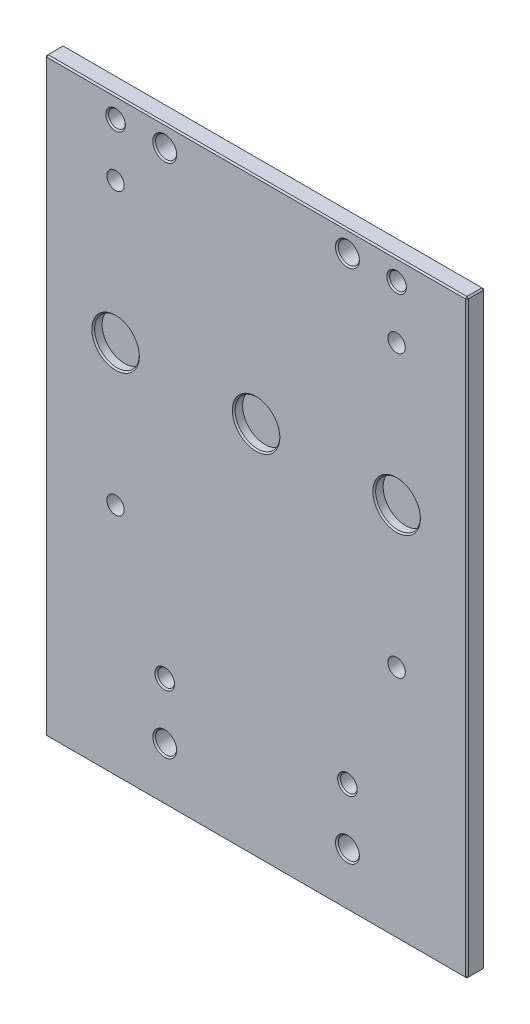
SolidWorks part; units mm, degrees
ref_plane "Front Plane" through (0, 0, 0) normal (0, 0, 1) x (1, 0, 0)
ref_plane "Top Plane" through (0, 0, 0) normal (0, 1, 0) x (1, 0, 0)
ref_plane "Right Plane" through (0, 0, 0) normal (1, 0, 0) x (0, 0, -1)
sketch "Sketch1" plane through (0, 0, 0) normal (0, 0, 1) x (1, 0, 0)
  line L2 (0, 0) -> (0, 210)
  line L3 (0, 210) -> (150, 210)
  line L4 (150, 0) -> (150, 210)
  line L7 (0, 0) -> (150, 0)
  circle A0 centre (25, 202.5) radius 2.98
  circle A1 centre (125, 202.5) radius 2.98
  circle A2 centre (42.5, 202.5) radius 3.75
  circle A3 centre (107.5, 202.5) radius 3.75
  circle A4 centre (107.5, 39) radius 2.98
  circle A5 centre (42.5, 39) radius 2.98
  circle A6 centre (42.5, 19) radius 3.75
  circle A7 centre (107.5, 19) radius 3.75
  dimension "D8" = 5.96
  dimension "D9" = 5.96
  dimension "D10" = 7.5
  dimension "D11" = 7.5
  dimension "D15" = 5.96
  dimension "D16" = 5.96
  dimension "D17" = 7.5
  dimension "D18" = 7.5
  dimension "D2" = 210
  dimension "D3" = 25
  dimension "D4" = 25
  dimension "D5" = 17.5
  dimension "D6" = 17.5
  dimension "D7" = 7.5
  dimension "D12" = 150
  dimension "D13" = 163.5
  dimension "D14" = 163.5
  dimension "D19" = 20
  dimension "D20" = 20
extrude "Boss-Extrude1" add sketch "Sketch1" along normal blind 6.35
sketch "Sketch2" plane through (0, 0, 6.35) normal (0, 0, 1) x (1, 0, 0)
  line L0 (150, 0) -> (150, 210) construction
  line L3 (0, 0) -> (150, 0) construction
  circle A0 centre (75, 133.75) radius 7.9577
  dimension "D1" = 15.9154
  dimension "D2" = 75
  dimension "D3" = 133.75
extrude "Cut-Extrude1" cut sketch "Sketch2" against normal blind 3.175
sketch "Sketch3" plane through (0, 0, 6.35) normal (0, 0, 1) x (1, 0, 0)
  circle A0 centre (25, 183.75) radius 3.1877
  circle A1 centre (125, 183.75) radius 3.1877
  circle A2 centre (125, 83.75) radius 3.1877
  circle A3 centre (25, 83.75) radius 3.1877
  circle A5 centre (75, 133.75) radius 7.9577 construction
  dimension "D1" = 6.3754
  dimension "D2" = 6.3754
  dimension "D3" = 6.3754
  dimension "D4" = 6.3754
  dimension "D9" = 50
  dimension "D8" = 50
  dimension "D10" = 50
  dimension "D5" = 50
  dimension "D6" = 50
  dimension "D7" = 50
  dimension "D11" = 50
  dimension "D12" = 50
hole_wizard "15/64 (0.23438) Diameter Hole1" positions "3DSketch1" profile "Sketch5" hole size "15/64" standard "Ansi Inch"
sketch3d "3DSketch1"
  point P0 (25, 183.75, 6.35)
  point P3 (125, 183.75, 6.35)
  point P6 (125, 83.75, 6.35)
  point P9 (25, 83.75, 6.35)
sketch "Sketch5" plane through (25, 183.75, 6.35) normal (1, 0, 0) x (0, -1, 0)
  line L0 (0, 0) -> (0, 9.2081)
  line L1 (0, 9.2081) -> (3.0924, 7.35)
  line L2 (3.0924, 7.35) -> (3.0924, 0)
  line L5 (3.0924, 0) -> (0, 0)
  line L10 (0, 9.2081) -> (-3.0925, 7.35) construction
  line L11 (0, -6.35) -> (0, 107.95) construction
  dimension "Hole Dia." = 6.1849
  dimension "Hole Depth" = 7.35
  dimension "Drill Angle" = 118
chamfer "Chamfer1" distance 0.5 angle 45 29 edges at (46.25, 202.5, 0) (27.98, 202.5, 0) (111.25, 202.5, 0) (127.98, 202.5, 0) (110.48, 39, 0) (111.25, 19, 0) (45.48, 39, 0) (46.25, 19, 0) (75, 0, 0) (0, 105, 0) (75, 210, 0) (150, 105, 0) (0, 210, 3.175) (150, 210, 3.175) (0, 0, 3.175) (150, 0, 3.175) (150, 105, 6.35) (75, 210, 6.35) (75, 0, 6.35) (0, 105, 6.35) (127.98, 202.5, 6.35) (111.25, 202.5, 6.35) (27.98, 202.5, 6.35) (46.25, 202.5, 6.35) (82.9577, 133.75, 6.35) (110.48, 39, 6.35) (111.25, 19, 6.35) (45.48, 39, 6.35) (46.25, 19, 6.35)
sketch "Sketch6" plane through (0, 0, 6.35) normal (0, 0, 1) x (1, 0, 0)
  circle A0 centre (125, 133.75) radius 7.9577
  circle A1 centre (25, 133.75) radius 7.9577
  circle A2 centre (125, 83.75) radius 3.0924 construction
  circle A3 centre (25, 83.75) radius 3.0924 construction
  circle A4 centre (25, 183.75) radius 3.0924 construction
  circle A5 centre (125, 183.75) radius 3.0924 construction
  circle A6 centre (125, 83.75) radius 3.0925
  circle A7 centre (25, 83.75) radius 3.0924
  circle A8 centre (25, 183.75) radius 3.0925
  circle A9 centre (125, 183.75) radius 3.0925
  circle A10 centre (75, 133.75) radius 7.9577 construction
  circle A11 centre (75, 133.75) radius 7.9577
  dimension "D1" = 15.9154
  dimension "D2" = 15.9154
extrude "Cut-Extrude2" cut sketch "Sketch6" against normal blind 3.175 contours A0 | A1
chamfer "Chamfer2" distance 0.5 angle 45 2 edges at (32.9577, 133.75, 6.35) (132.9577, 133.75, 6.35)
